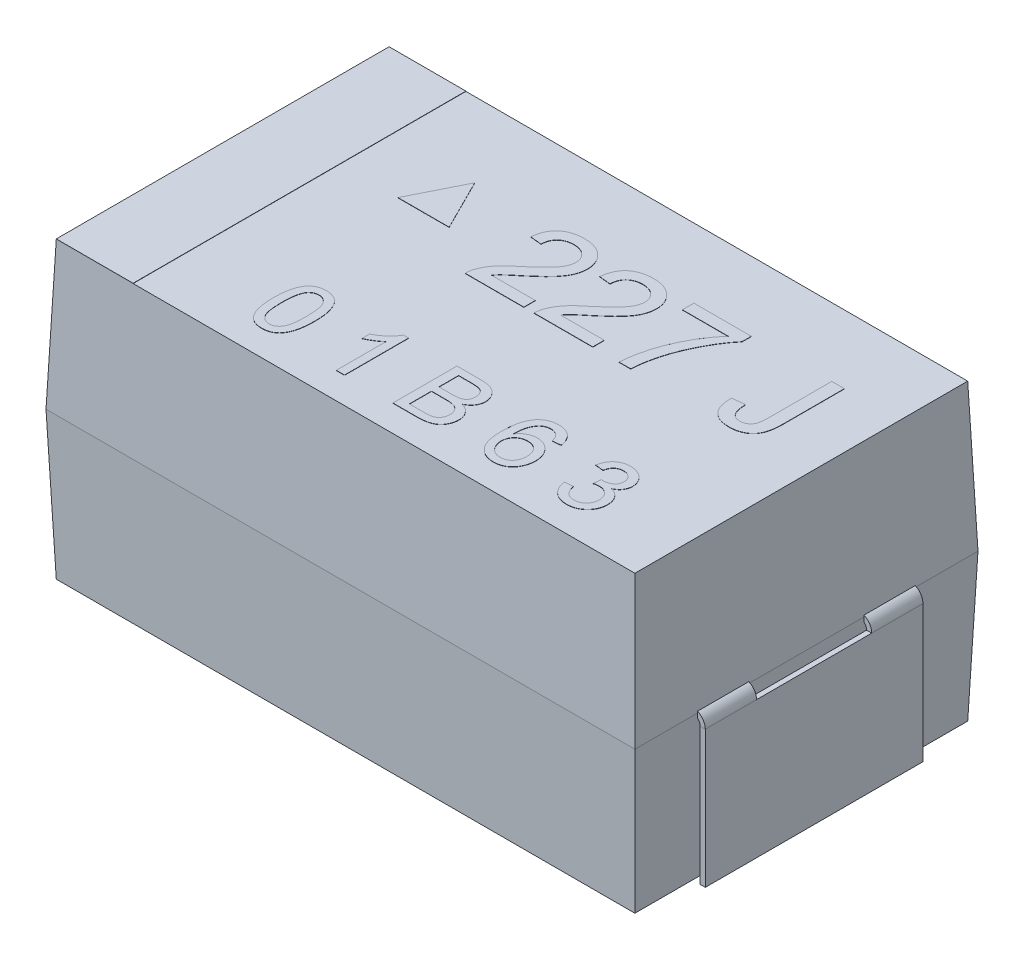
SolidWorks part; units mm, degrees
ref_plane "Front Plane" through (0, 0, 0) normal (0, 0, 1) x (1, 0, 0)
ref_plane "Top Plane" through (0, 0, 0) normal (0, 1, 0) x (1, 0, 0)
ref_plane "Right Plane" through (0, 0, 0) normal (1, 0, 0) x (0, 0, -1)
sketch "Sketch1" plane through (0, 0, 0) normal (0, 1, 0) x (1, 0, 0)
  line L1 (-2.921, 1.7018) -> (2.921, 1.7018)
  line L2 (-2.921, 1.7018) -> (-2.921, -1.7018)
  line L3 (-2.921, -1.7018) -> (2.921, -1.7018)
  line L4 (2.921, 1.7018) -> (2.921, -1.7018)
  line L5 (-2.921, 1.7018) -> (2.921, -1.7018) construction
  line L6 (-2.921, -1.7018) -> (2.921, 1.7018) construction
  point P0 (0, 0)
  dimension "D1" = 3.4036
  dimension "D2" = 5.842
extrude "Boss-Extrude1" add sketch "Sketch1" along normal mid plane 2.921
sketch "Sketch2" plane through (0, 0, 0) normal (1, 0, 0) x (0, 0, -1)
  line L0 (-1.7018, 0) -> (-1.6508, 1.4605)
  line L1 (-1.7018, 1.4605) -> (-1.7018, -1.4605) construction
  line L2 (-1.7018, 1.4605) -> (1.7018, 1.4605) construction
  line L3 (-1.6508, 1.4605) -> (-1.7018, 1.4605)
  line L4 (-1.7018, 1.4605) -> (-1.7018, 0)
  line L5 (1.6508, 1.4605) -> (1.7018, 0)
  line L6 (1.7018, 1.4605) -> (1.7018, -1.4605) construction
  line L7 (1.7018, 0) -> (1.7018, 1.4605)
  line L8 (1.7018, 1.4605) -> (1.6508, 1.4605)
  dimension "D1" = 2
extrude "Cut-Extrude1" cut sketch "Sketch2" against normal through all both and the other way through all
mirror "Mirror1" about plane through (0, 0, 0) normal (0, 1, 0) of "Cut-Extrude1"
sketch "Sketch3" plane through (0, 0, 0) normal (0, 0, 1) x (1, 0, 0)
  line L0 (-2.921, 0) -> (-2.921, 1.4605)
  line L1 (-2.921, 0) -> (2.921, 0) construction
  line L2 (-2.921, 1.4605) -> (-2.87, 1.4605)
  line L3 (-2.921, 1.4605) -> (2.921, 1.4605) construction
  line L4 (-2.87, 1.4605) -> (-2.921, 0)
  line L5 (-2.921, 0) -> (-2.921, 1.4605) construction
  line L6 (2.921, 0) -> (2.921, 1.4605)
  line L7 (2.921, 1.4605) -> (2.87, 1.4605)
  line L8 (2.87, 1.4605) -> (2.921, 0)
  dimension "D1" = 2
extrude "Cut-Extrude2" cut sketch "Sketch3" against normal through all both and the other way through all
mirror "Mirror2" about plane through (0, 0, 0) normal (0, 1, 0) of "Cut-Extrude2"
ref_plane "Plane2" through (2.87, 0, 0) normal (1, 0, 0) x (0, 0, -1)
sketch "Sketch4" plane through (2.87, 0, 0) normal (1, 0, 0) x (0, 0, -1)
  line L0 (1.7018, 0) -> (-1.7018, 0) construction
  line L1 (-1.0795, 0.0254) -> (-0.5715, 0.0254)
  line L2 (-1.0795, 0.0254) -> (-1.0795, -0.0254)
  line L3 (-1.0795, -0.0254) -> (-0.5715, -0.0254)
  line L4 (-0.5715, 0.0254) -> (-0.5715, -0.0254)
  line L5 (0.5715, 0.0254) -> (1.0795, 0.0254)
  line L6 (0.5715, 0.0254) -> (0.5715, -0.0254)
  line L7 (0.5715, -0.0254) -> (1.0795, -0.0254)
  line L8 (1.0795, 0.0254) -> (1.0795, -0.0254)
  line L9 (-0.5715, 0.0254) -> (0.5715, 0.0254) construction
  point P10 (0, 0)
  point P11 (1.0795, 0)
  point P12 (0, 0.0254)
  dimension "D1" = 0.0508
  dimension "D2" = 0.508
  dimension "D3" = 2.159
sketch "Sketch5" plane through (0, 0, 0) normal (0, 0, 1) x (1, 0, 0)
  line L0 (2.87, -0.0254) -> (2.9462, -0.0254) construction
  line L1 (2.9462, -0.0254) -> (2.9462, -0.1016) construction
  line L2 (2.9462, -0.1016) -> (2.9462, -1.4605)
  line L3 (-2.87, -1.4605) -> (2.87, -1.4605) construction
  arc A0 (2.87, -0.0254) -> (2.9462, -0.1016) centre (2.87, -0.1016) cw
  dimension "D1" = 0.0762
ref_plane "Plane3" through (-2.87, 0, 0) normal (1, 0, 0) x (0, 0, -1)
sketch "Sketch6" plane through (-2.87, 0, 0) normal (1, 0, 0) x (0, 0, -1)
  line L0 (-1.0795, 0.0254) -> (-1.0795, -0.0254) construction
  line L1 (1.0795, 0.0254) -> (0.5715, 0.0254)
  line L2 (1.0795, 0.0254) -> (1.0795, -0.0254)
  line L3 (1.0795, -0.0254) -> (0.5715, -0.0254)
  line L4 (0.5715, 0.0254) -> (0.5715, -0.0254)
  line L5 (-0.5715, 0.0254) -> (-1.0795, 0.0254)
  line L6 (-0.5715, 0.0254) -> (-0.5715, -0.0254)
  line L7 (-0.5715, -0.0254) -> (-1.0795, -0.0254)
  line L8 (-1.0795, 0.0254) -> (-1.0795, -0.0254)
  line L9 (-1.0795, 0.0254) -> (-0.5715, 0.0254) construction
  line L10 (0.5715, 0.0254) -> (1.0795, 0.0254) construction
  line L11 (1.0795, 0.0254) -> (1.0795, -0.0254) construction
sketch "Sketch7" plane through (0, 0, 0) normal (0, 0, 1) x (1, 0, 0)
  line L0 (-2.87, -0.0254) -> (-2.9462, -0.0254) construction
  line L1 (-2.9462, -0.0254) -> (-2.9462, -0.1016) construction
  line L2 (-2.9462, -0.1016) -> (-2.9462, -1.4605)
  line L3 (2.87, -0.0254) -> (2.9462, -0.0254) construction
  arc A0 (-2.87, -0.0254) -> (-2.9462, -0.1016) centre (-2.87, -0.1016) ccw
sweep "Sweep1" add profiles "Sketch4" path "Sketch5"
sweep "Sweep2" add profiles "Sketch6" path "Sketch7"
sketch "Sketch8" plane through (2.997, 0, 0) normal (1, 0, 0) x (0, 0, -1)
  line L1 (-0.5715, -0.1016) -> (0.5715, -0.1016)
  line L2 (-0.5715, -0.1016) -> (-0.5715, -1.4605)
  line L3 (-0.5715, -1.4605) -> (0.5715, -1.4605)
  line L4 (0.5715, -0.1016) -> (0.5715, -1.4605)
extrude "Boss-Extrude2" add sketch "Sketch8" against normal up to surface (0.0508 mm away) up to face at (2.9462, -0.781, 0.8255)
sketch "Sketch9" plane through (-2.997, 0, 0) normal (-1, 0, 0) x (0, 0, 1)
  line L0 (0.5715, -0.1016) -> (0.5715, -1.4605) construction
  line L1 (-0.5715, -1.4605) -> (0.5715, -1.4605)
  line L2 (-0.5715, -1.4605) -> (-0.5715, -0.9525)
  line L3 (-0.5715, -0.9525) -> (0.5715, -0.9525)
  line L4 (0.5715, -1.4605) -> (0.5715, -0.9525)
  dimension "D1" = 0.508
extrude "Boss-Extrude3" add sketch "Sketch9" against normal up to surface (0.0508 mm away) up to face at (-2.9462, -0.781, 0.8255)
sketch "Sketch10" plane through (0, 1.4605, 0) normal (0, 1, 0) x (1, 0, 0)
  line L0 (-2.87, -1.6508) -> (2.87, -1.6508) construction
  line L1 (-2.87, -1.6508) -> (-2.108, -1.6508)
  line L2 (-2.87, -1.6508) -> (-2.87, 1.6508)
  line L3 (-2.87, 1.6508) -> (-2.108, 1.6508)
  line L4 (-2.108, -1.6508) -> (-2.108, 1.6508)
  line L5 (-2.87, 1.6508) -> (2.87, 1.6508) construction
  line L6 (-2.87, 1.6508) -> (-2.87, -1.6508) construction
  dimension "D1" = 0.762
extrude "Boss-Extrude4" add sketch "Sketch10" along normal blind 0.0025
sketch "Sketch11" plane through (0, 1.4605, 0) normal (0, 1, 0) x (1, 0, 0)
  line L0 (-1.5303, 0.399) -> (-1.2763, 0.907)
  line L1 (-1.2763, 0.907) -> (-1.0223, 0.399)
  line L2 (-1.0223, 0.399) -> (-1.5303, 0.399)
  line L3 (-0.5805, 0.0824) -> (2.1661, 0.0824) construction
  line L4 (-1.889, -1.3906) -> (2.7478, -1.3906) construction
  text T0 "227 J" height 0.889
  text T1 "0 1 B 6 3" font "Arial" height 0.635
  point P6 (2.7478, -1.3906)
  point P7 (-1.889, -1.3817)
  dimension "D1" = 0.508
  dimension "D2" = 0.508
extrude "Boss-Extrude5" add sketch "Sketch11" along normal blind 0.0025
